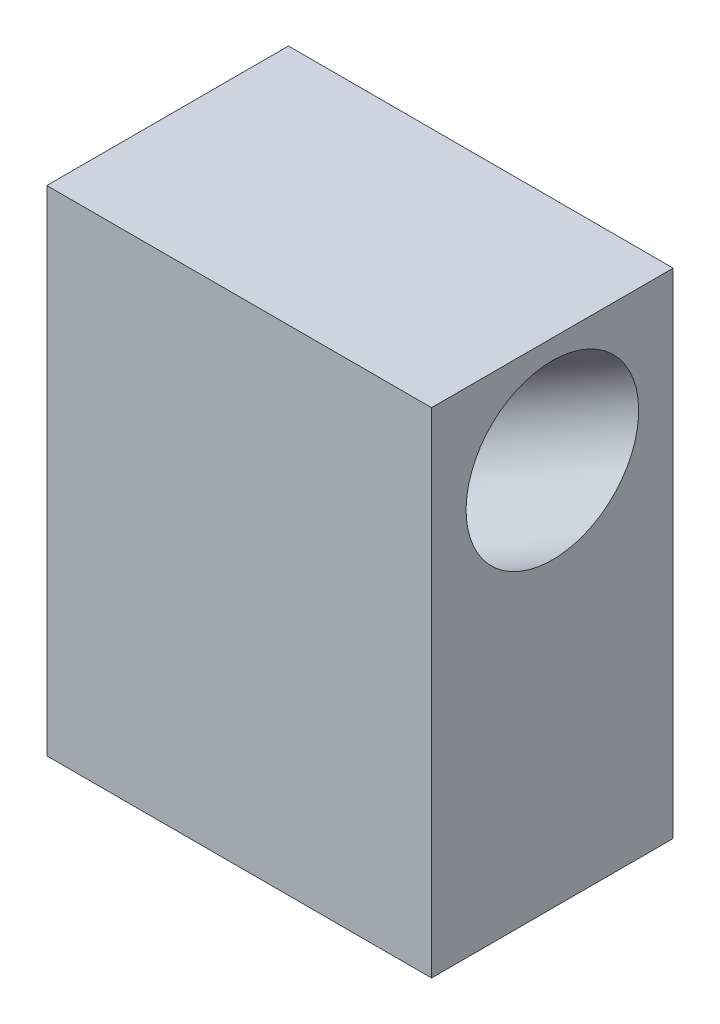
SolidWorks part; units mm, degrees
ref_plane "Front Plane" through (0, 0, 0) normal (0, 0, 1) x (1, 0, 0)
ref_plane "Top Plane" through (0, 0, 0) normal (0, 1, 0) x (1, 0, 0)
ref_plane "Right Plane" through (0, 0, 0) normal (1, 0, 0) x (0, 0, -1)
sketch "Sketch1" plane through (0, 0, 0) normal (0, 0, 1) x (1, 0, 0)
  line L0 (0, 1.737) -> (0, 38.0812) construction
  line L1 (0, 38.0812) -> (28.3097, 38.0812) construction
  line L2 (28.3097, 38.0812) -> (28.3097, 1.737) construction
  line L3 (28.3097, 1.737) -> (0, 1.737) construction
  line L4 (28.3097, 27.1677) -> (0, 10.8231) construction
  line L6 (0, 38.0812) -> (28.3097, 38.0812)
  line L7 (0, 38.0812) -> (0, 1.737)
  line L8 (0, 1.737) -> (28.3097, 1.737)
  line L9 (28.3097, 38.0812) -> (28.3097, 1.737)
  dimension "D1" = 30
extrude "Boss-Extrude1" add sketch "Sketch1" along normal blind 17.78 contours L6 L9 L8 L7
sketch "Sketch2" plane through (28.3097, 0, 0) normal (1, 0, 0) x (0, 0, -1)
  line L0 (-8.89, 38.0812) -> (-8.89, 1.737) construction
  line L1 (-17.78, 38.0812) -> (0, 38.0812) construction
  line L2 (-17.78, 1.737) -> (0, 1.737) construction
  circle A0 centre (-8.89, 30.2809) radius 6.35
  point P8 (-8.89, 30.2809)
  dimension "D1" = 12.7
ref_plane "Plane1" through (37.7219, 21.7787, 0) normal (0.866, 0.5, 0) x (0, 0, -1)
ref_plane "Plane2" through (0.7522, 0.4343, 0) normal (-0.866, -0.5, 0) x (0, 0, -1)
extrude "Cut-Extrude2" cut sketch "Sketch2" along direction (0.866, 0.5, 0) on the side against the normal up to surface (32.6892 mm away) from surface at 0 starting at face at (28.3097, 19.9091, 8.89)
